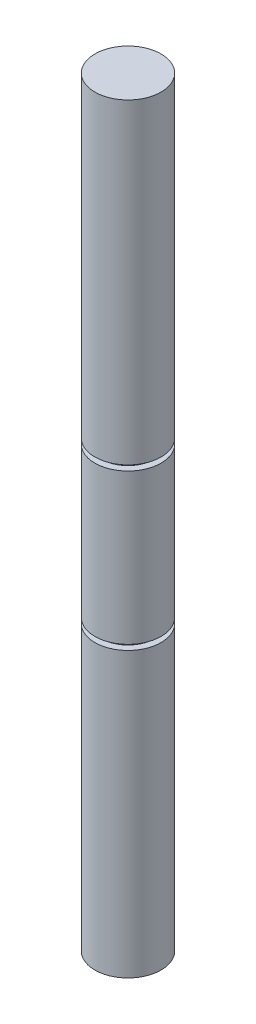
SolidWorks part; units mm, degrees
ref_plane "Front Plane" through (0, 0, 0) normal (0, 0, 1) x (1, 0, 0)
ref_plane "Top Plane" through (0, 0, 0) normal (0, 1, 0) x (1, 0, 0)
ref_plane "Right Plane" through (0, 0, 0) normal (1, 0, 0) x (0, 0, -1)
sketch "Sketch1" plane through (0, 0, 0) normal (0, 1, 0) x (1, 0, 0)
  circle A0 centre (0, 0) radius 5
  dimension "D1" = 10
extrude "Boss-Extrude1" add sketch "Sketch1" along normal blind 115
sketch "Sketch2" plane through (0, 0, 0) normal (1, 0, 0) x (0, 0, -1)
  line L0 (5, 0) -> (5, 115) construction
  line L1 (5, 67.2) -> (4, 67.2)
  line L2 (5, 67.2) -> (5, 66.4)
  line L3 (5, 66.4) -> (4, 66.4)
  line L4 (4, 67.2) -> (4, 66.4)
  line L5 (0, 115) -> (0, 83.5859) construction
  line L6 (5, 115) -> (-5, 115) construction
  dimension "D1" = 0.8
  dimension "D2" = 1
  dimension "D3" = 47.8
revolve "Cut-Revolve1" cut sketch "Sketch2" angle 360 about L5
pattern_linear "LPattern1" count 2 spacing 23.5 along (0, -1, 0) of "Cut-Revolve1"
